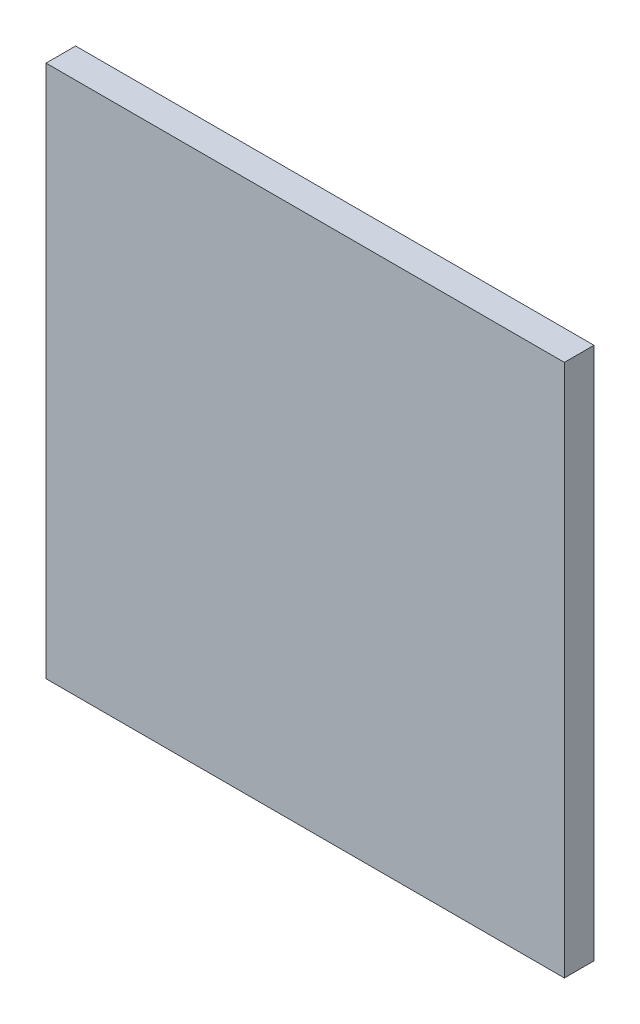
SolidWorks part; units mm, degrees
ref_plane "前视基准面" through (0, 0, 0) normal (0, 0, 1) x (1, 0, 0)
ref_plane "上视基准面" through (0, 0, 0) normal (0, 1, 0) x (1, 0, 0)
ref_plane "右视基准面" through (0, 0, 0) normal (1, 0, 0) x (0, 0, -1)
sketch "草图1" plane through (0, 0, 0) normal (0, 0, 1) x (1, 0, 0)
  line L1 (-17.5, 18) -> (17.5, 18)
  line L2 (-17.5, 18) -> (-17.5, -18)
  line L3 (-17.5, -18) -> (17.5, -18)
  line L4 (17.5, 18) -> (17.5, -18)
  line L5 (-17.5, 18) -> (17.5, -18) construction
  line L6 (-17.5, -18) -> (17.5, 18) construction
  point P0 (0, 0)
  dimension "D1" = 35
  dimension "D2" = 36
extrude "凸台-拉伸1" add sketch "草图1" along normal blind 2
